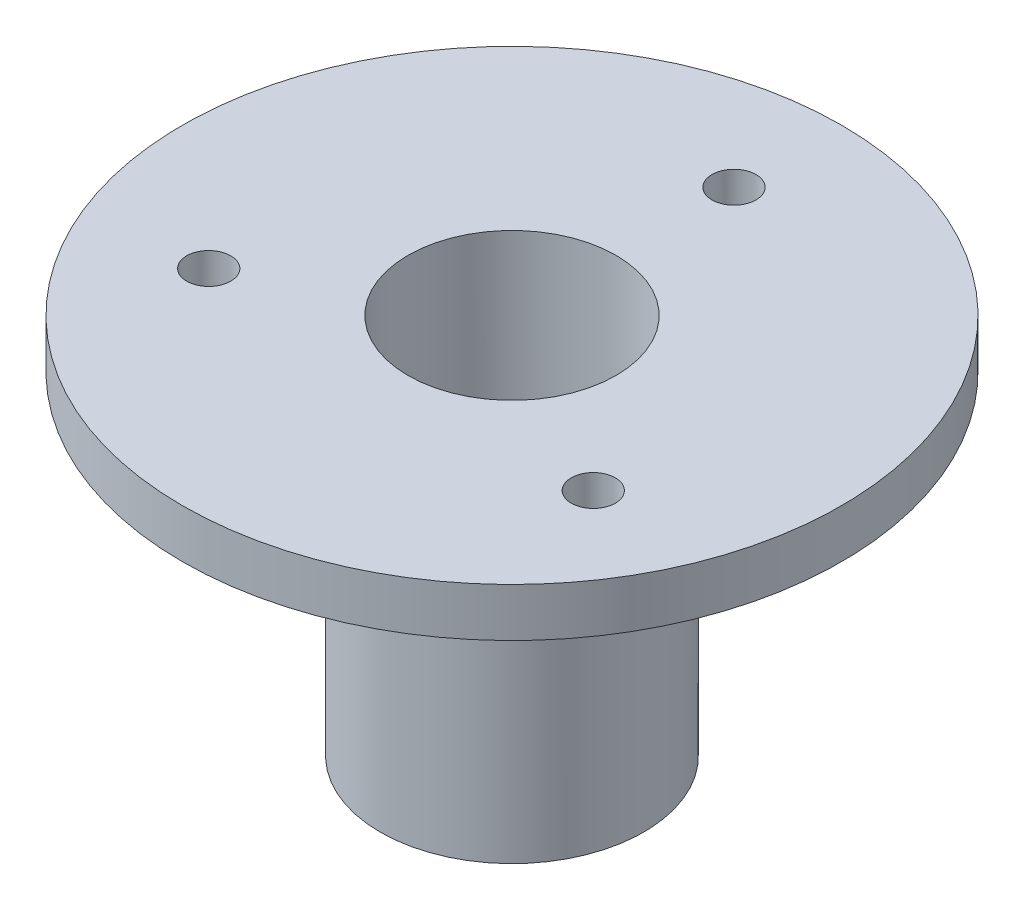
SolidWorks part; units mm, degrees
ref_plane "Alzado" through (0, 0, 0) normal (0, 0, 1) x (1, 0, 0)
ref_plane "Planta" through (0, 0, 0) normal (0, 1, 0) x (1, 0, 0)
ref_plane "Vista lateral" through (0, 0, 0) normal (1, 0, 0) x (0, 0, -1)
sketch "Croquis1" plane through (0, 0, 0) normal (0, 1, 0) x (1, 0, 0)
  line L0 (0, 0) -> (0, 32) construction
  circle A0 centre (0, 0) radius 47.5
  circle A1 centre (0, 32) radius 3.175
  circle A2 centre (27.7128, -16) radius 3.175
  circle A3 centre (-27.7128, -16) radius 3.175
  circle A4 centre (0, 0) radius 15
  point P11 (0, 0)
  dimension "D1" = 95
  dimension "D2" = 6.35
  dimension "D6" = 30
  dimension "D3" = 32
  dimension "D5" = 32
  dimension "D4" = 3
extrude "Saliente-Extruir1" add sketch "Croquis1" along normal blind 7
sketch "Croquis2" plane through (0, 0, 0) normal (0, -1, 0) x (1, 0, 0)
  circle A0 centre (0, 0) radius 15
  circle A1 centre (0, 0) radius 19
  dimension "D1" = 30
  dimension "D2" = 38
extrude "Saliente-Extruir2" add sketch "Croquis2" along normal blind 48
sketch "Croquis3" plane through (0, 0, 0) normal (0, -1, 0) x (1, 0, 0)
  circle A0 centre (-27.7128, 16) radius 7.5
  circle A1 centre (27.7128, 16) radius 7.5
  circle A2 centre (0, -32) radius 7.5
  circle A3 centre (-27.7128, 16) radius 3.175
  circle A4 centre (27.7128, 16) radius 3.175
  circle A5 centre (0, -32) radius 3.175
  dimension "D1" = 15
  dimension "D2" = 15
  dimension "D3" = 15
  dimension "D4" = 6.35
  dimension "D5" = 6.35
  dimension "D6" = 6.35
extrude "Saliente-Extruir3" add sketch "Croquis3" along normal blind 3
